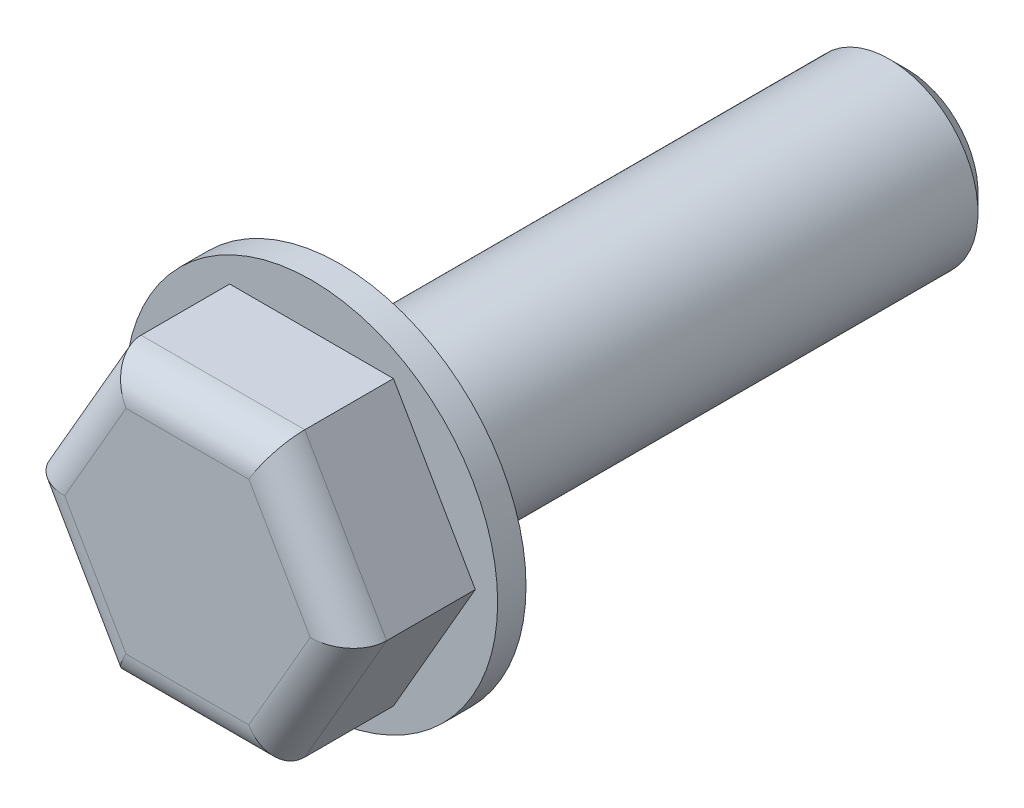
SolidWorks part; units mm, degrees
ref_plane "Спереди" through (0, 0, 0) normal (0, 0, 1) x (1, 0, 0)
ref_plane "Сверху" through (0, 0, 0) normal (0, 1, 0) x (1, 0, 0)
ref_plane "Справа" through (0, 0, 0) normal (1, 0, 0) x (0, 0, -1)
other "Configuration Table"
sketch "Эскиз2" plane through (0, 0, 0) normal (0, 0, 1) x (1, 0, 0)
  circle A0 centre (0, 0) radius 5.25
  dimension "D1" = 10.5
extrude "Бобышка-Вытянуть1" add sketch "Эскиз2" along normal blind 0.8
sketch "Эскиз3" plane through (0, 0, 0.8) normal (0, 0, 1) x (1, 0, 0)
  line L1 (-2.3094, 4) -> (-4.6188, 0)
  line L2 (-4.6188, 0) -> (-2.3094, -4)
  line L3 (-2.3094, -4) -> (2.3094, -4)
  line L4 (2.3094, -4) -> (4.6188, 0)
  line L5 (4.6188, 0) -> (2.3094, 4)
  line L6 (2.3094, 4) -> (-2.3094, 4)
  circle A0 centre (0, 0) radius 4 construction
  dimension "D1" = 8
extrude "Бобышка-Вытянуть2" add sketch "Эскиз3" along normal blind 3.5
sketch "Эскиз4" plane through (0, 0, 0) normal (0, 0, -1) x (-1, 0, 0)
  circle A0 centre (0, 0) radius 2.5
  dimension "D1" = 5
extrude "Бобышка-Вытянуть3" add sketch "Эскиз4" along normal blind 16
fillet "Скругление1" radius 1 6 edges at (3.4641, 2, 4.3) (3.4641, -2, 4.3) (0, -4, 4.3) (-3.4641, -2, 4.3) (-3.4641, 2, 4.3) (0, 4, 4.3)
chamfer "Фаска1" distance 0.5 angle 45 1 edges at (-2.5, 0, -16)
